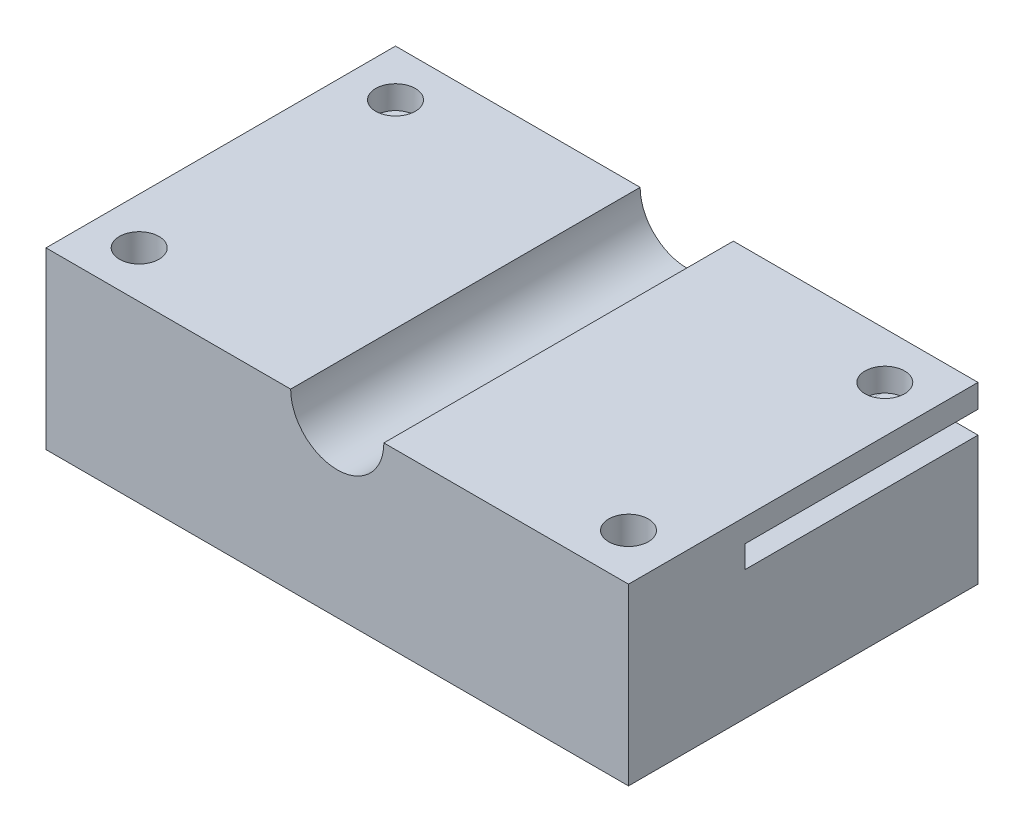
SolidWorks part; units mm, degrees
ref_plane "Piano frontale" through (0, 0, 0) normal (0, 0, 1) x (1, 0, 0)
ref_plane "Piano superiore" through (0, 0, 0) normal (0, 1, 0) x (1, 0, 0)
ref_plane "Piano destro" through (0, 0, 0) normal (1, 0, 0) x (0, 0, -1)
sketch "Schizzo1" plane through (0, 0, 0) normal (0, 0, 1) x (1, 0, 0)
  line L1 (0, 25.1256) -> (50, 25.1256)
  line L2 (0, 25.1256) -> (0, 10.1256)
  line L3 (0, 10.1256) -> (50, 10.1256)
  line L4 (50, 25.1256) -> (50, 10.1256)
  dimension "D1" = 15
  dimension "D2" = 50
extrude "Estrusione-Estrusione1" add sketch "Schizzo1" along normal blind 30
sketch "Schizzo2" plane through (0, 0, 0) normal (0, 0, 1) x (1, 0, 0)
  line L0 (16.5442, 23.1256) -> (-0.7895, 23.1256)
  line L1 (-0.7895, 23.1256) -> (-0.7895, 21.2056)
  line L2 (-0.7895, 21.2056) -> (7.2662, 21.2056)
  line L3 (50, 25.1256) -> (0, 25.1256) construction
  line L4 (7.2662, 21.2056) -> (7.757, 21.1735)
  line L5 (7.757, 21.1735) -> (8.2394, 21.0775)
  line L6 (8.2394, 21.0775) -> (8.7051, 20.9194)
  line L7 (8.7051, 20.9194) -> (9.1462, 20.7019)
  line L8 (9.1462, 20.7019) -> (9.5552, 20.4286)
  line L9 (9.5552, 20.4286) -> (9.925, 20.1043)
  line L10 (9.925, 20.1043) -> (10.2493, 19.7346)
  line L11 (10.2493, 19.7346) -> (10.5225, 19.3256)
  line L12 (10.5225, 19.3256) -> (10.74, 18.8845)
  line L13 (10.74, 18.8845) -> (10.8981, 18.4188)
  line L14 (10.8981, 18.4188) -> (10.9941, 17.9364)
  line L15 (10.9941, 17.9364) -> (11.2143, 16.0169)
  line L16 (11.2143, 16.0169) -> (11.7658, 14.6856)
  line L17 (25, 29.3345) -> (25, -10.4001) construction
  line L18 (38.7857, 16.0169) -> (38.2342, 14.6856)
  line L19 (39.0059, 17.9364) -> (38.7857, 16.0169)
  line L20 (39.1019, 18.4188) -> (39.0059, 17.9364)
  line L21 (39.26, 18.8845) -> (39.1019, 18.4188)
  line L22 (39.4775, 19.3256) -> (39.26, 18.8845)
  line L23 (39.7507, 19.7346) -> (39.4775, 19.3256)
  line L24 (40.075, 20.1043) -> (39.7507, 19.7346)
  line L25 (40.4448, 20.4286) -> (40.075, 20.1043)
  line L26 (40.8538, 20.7019) -> (40.4448, 20.4286)
  line L27 (41.2949, 20.9194) -> (40.8538, 20.7019)
  line L28 (41.7606, 21.0775) -> (41.2949, 20.9194)
  line L29 (42.243, 21.1735) -> (41.7606, 21.0775)
  line L30 (42.7338, 21.2056) -> (42.243, 21.1735)
  line L31 (50.7895, 21.2056) -> (42.7338, 21.2056)
  line L32 (50.7895, 23.1256) -> (50.7895, 21.2056)
  line L33 (33.4558, 23.1256) -> (50.7895, 23.1256)
  arc A0 (16.5442, 23.1256) -> (11.7658, 14.6856) centre (16.5442, 17.5529) cw
  circle A1 centre (16.5442, 17.5529) radius 4.0834
  circle A4 centre (33.4558, 17.5529) radius 4.0834
  arc A5 (33.4558, 23.1256) -> (38.2342, 14.6856) centre (33.4558, 17.5529) ccw
  point P4 (25, 25.1256)
  point P7 (16.5442, 13.4695)
  point P8 (16.5442, 11.9802)
  dimension "D1" = 2
extrude "Taglio-Estrusione1" cut sketch "Schizzo2" along normal blind 20 contours A0 L0 L1 L2 L4 L5 L6 L7 L8 L9 L10 L11 L12 L13 L14 L15 L16 A1 | L33 A5 L18 L19 L20 L21 L22 L23 L24 L25 L26 L27 L28 L29 L30 L31 L32 A4
sketch "Schizzo6" plane through (0, 25.1256, 0) normal (0, 1, 0) x (1, 0, 0)
  line L0 (25, 0) -> (25, -30) construction
  line L1 (50, 0) -> (0, 0) construction
  line L2 (50, -30) -> (0, -30) construction
  line L3 (0, -15) -> (50, -15) construction
  line L4 (0, -30) -> (0, 0) construction
  line L5 (50, -30) -> (50, 0) construction
  circle A1 centre (4, -4) radius 1.7
  circle A2 centre (46, -4) radius 1.7
  circle A3 centre (46, -26) radius 1.7
  circle A4 centre (4, -26) radius 1.7
  point P20 (6.695, 0)
  point P21 (0, -6.2)
  dimension "D1" = 3.4
  dimension "D2" = 4
  dimension "D3" = 4
extrude "Taglio-Estrusione3" cut sketch "Schizzo6" against normal blind 30
sketch "Schizzo9" plane through (0, 0, 0) normal (0, 0, -1) x (-1, 0, 0)
  line L0 (-50, 25.1256) -> (0, 25.1256) construction
  circle A0 centre (-25, 25.1256) radius 4
  dimension "D1" = 8
extrude "Taglio-Estrusione5" cut sketch "Schizzo9" against normal through all
